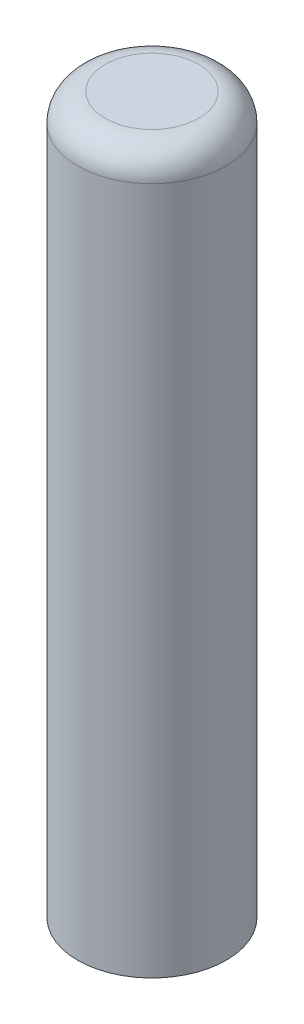
SolidWorks part; units mm, degrees
ref_plane "Front Plane" through (0, 0, 0) normal (0, 0, 1) x (1, 0, 0)
ref_plane "Top Plane" through (0, 0, 0) normal (0, 1, 0) x (1, 0, 0)
ref_plane "Right Plane" through (0, 0, 0) normal (1, 0, 0) x (0, 0, -1)
sketch "Sketch1" plane through (0, 0, 0) normal (0, 1, 0) x (1, 0, 0)
  circle A0 centre (0, 0) radius 1.35
  dimension "D1" = 2.7
extrude "Boss-Extrude1" add sketch "Sketch1" along normal blind 8 and the other way blind 5
fillet "Fillet1" radius 0.5 1 edges at (0, 8, 1.35)
